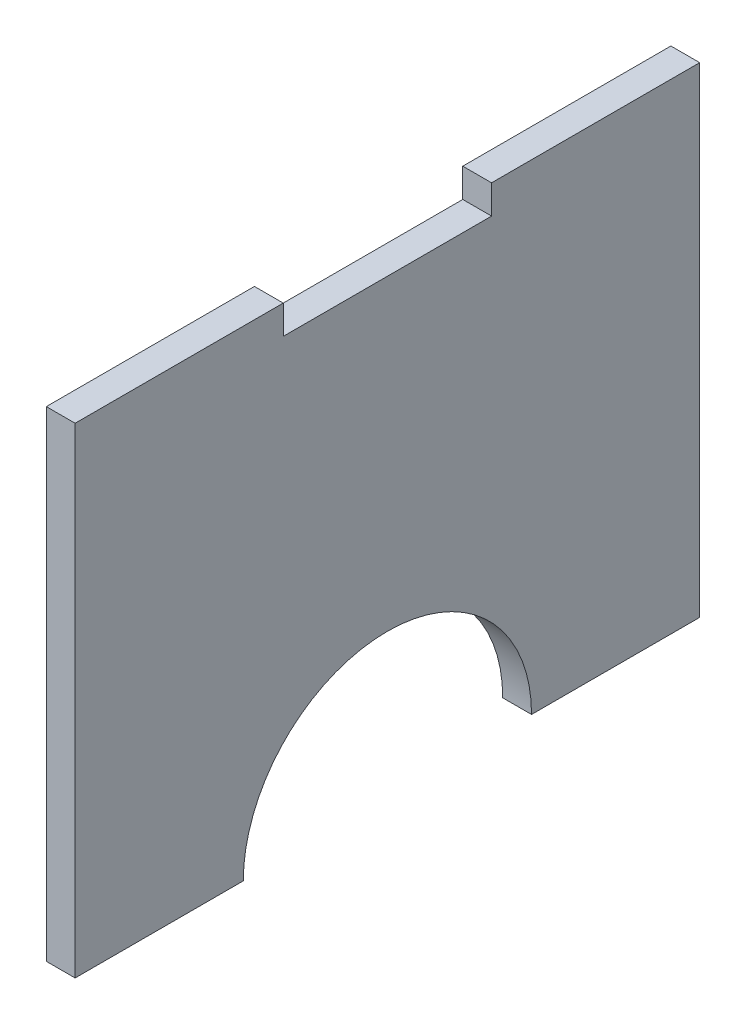
SolidWorks part; units mm, degrees
ref_plane "Front Plane" through (0, 0, 0) normal (0, 0, 1) x (1, 0, 0)
ref_plane "Top Plane" through (0, 0, 0) normal (0, 1, 0) x (1, 0, 0)
ref_plane "Right Plane" through (0, 0, 0) normal (1, 0, 0) x (0, 0, -1)
sketch "Sketch1" plane through (0, 0, 0) normal (1, 0, 0) x (0, 0, -1)
  line L0 (-32.5, 50) -> (-32.5, 0)
  line L2 (32.5, 0) -> (32.5, 50)
  line L8 (-32.5, 0) -> (-15, 0)
  line L9 (32.5, 0) -> (15, 0)
  line L10 (-32.5, 50) -> (-10.84, 50)
  line L11 (-10.84, 50) -> (-10.84, 47)
  line L12 (-10.84, 47) -> (10.84, 47)
  line L13 (10.84, 47) -> (10.84, 50)
  line L14 (10.84, 50) -> (32.5, 50)
  arc A1 (-15, 0) -> (15, 0) centre (0, 0) cw
  dimension "D2" = 15
  dimension "D1" = 65
  dimension "D3" = 3
  dimension "D4" = 21.68
extrude "Boss-Extrude1" add sketch "Sketch1" along normal blind 3
